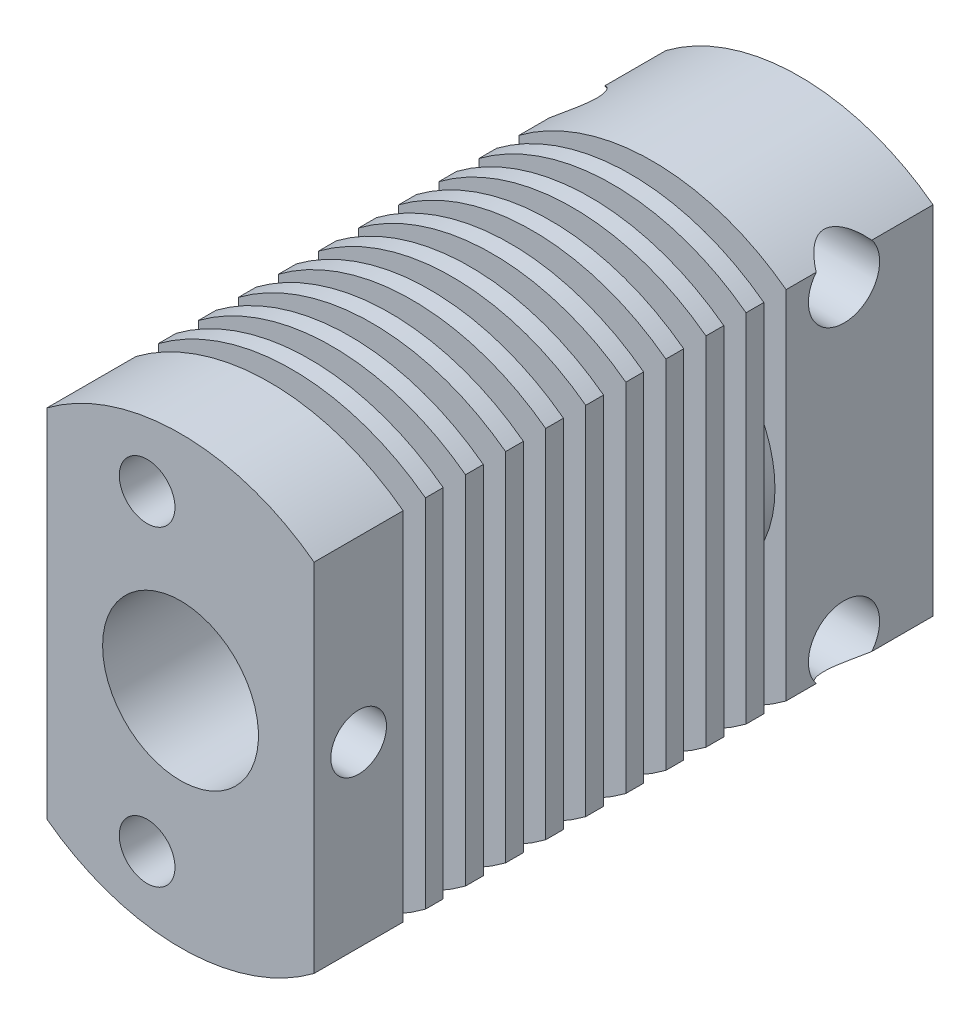
SolidWorks part; units mm, degrees
material "4032-T6"
ref_plane "Alzado" through (0, 0, 0) normal (0, 0, 1) x (1, 0, 0)
ref_plane "Planta" through (0, 0, 0) normal (0, 1, 0) x (1, 0, 0)
ref_plane "Vista lateral" through (0, 0, 0) normal (1, 0, 0) x (0, 0, -1)
sketch "Croquis1" plane through (0, 0, 0) normal (0, 1, 0) x (1, 0, 0)
  line L0 (4.3, -9.8) -> (0, -9.8)
  line L1 (0, -9.8) -> (0, -10.8)
  line L2 (0, -10.8) -> (4.3, -10.8)
  line L3 (4.3, -10.8) -> (4.3, -9.8)
  line L4 (0, -9.8) -> (0, -10.8) construction
revolve "Revolución1" add sketch "Croquis1" angle 360 about L4
ref_plane "Plano1" through (0, 0, 9.8) normal (0, 0, 1) x (1, 0, 0)
sketch "Croquis2" plane through (0, 0, 9.8) normal (0, 0, 1) x (1, 0, 0)
  line L0 (-6, 8) -> (-6, -8)
  line L1 (6, -8) -> (6, 8)
  arc A0 (6, 8) -> (-6, 8) centre (0, 0) ccw
  arc A1 (-6, -8) -> (6, -8) centre (0, 0) ccw
extrude "Saliente-Extruir1" add sketch "Croquis2" against normal blind 0.8
ref_plane "Plano2" through (0, 0, 10.8) normal (0, 0, -1) x (-1, 0, 0)
sketch "Croquis3" plane through (0, 0, 10.8) normal (0, 0, -1) x (-1, 0, 0)
  line L0 (6, -8) -> (6, 8)
  line L1 (-6, 8) -> (-6, -8)
  arc A0 (6, 8) -> (-6, 8) centre (0, 0) ccw
  arc A1 (-6, -8) -> (6, -8) centre (0, 0) ccw
extrude "Saliente-Extruir2" add sketch "Croquis3" against normal blind 0.8
sketch "Croquis4" plane through (0, 0, 11.6) normal (0, 0, 1) x (1, 0, 0)
  circle A0 centre (0, 0) radius 4.3
extrude "Saliente-Extruir3" add sketch "Croquis4" along normal blind 1
sketch "Croquis5" plane through (0, 0, 9) normal (0, 0, -1) x (-1, 0, 0)
  circle A0 centre (0, 0) radius 4.3
extrude "Saliente-Extruir4" add sketch "Croquis5" along normal blind 1
ref_plane "Plano3" through (0, 0, 8) normal (0, 0, 1) x (1, 0, 0)
sketch "Croquis6" plane through (0, 0, 8) normal (0, 0, 1) x (1, 0, 0)
  line L0 (-6, 8) -> (-6, -8)
  line L1 (6, -8) -> (6, 8)
  arc A0 (6, 8) -> (-6, 8) centre (0, 0) ccw
  arc A1 (-6, -8) -> (6, -8) centre (0, 0) ccw
extrude "Saliente-Extruir5" add sketch "Croquis6" against normal blind 0.8
ref_plane "Plano4" through (0, 0, 12.6) normal (0, 0, -1) x (-1, 0, 0)
sketch "Croquis7" plane through (0, 0, 12.6) normal (0, 0, -1) x (-1, 0, 0)
  line L0 (6, -8) -> (6, 8)
  line L1 (-6, 8) -> (-6, -8)
  arc A0 (6, 8) -> (-6, 8) centre (0, 0) ccw
  arc A1 (-6, -8) -> (6, -8) centre (0, 0) ccw
extrude "Saliente-Extruir6" add sketch "Croquis7" against normal blind 0.8
sketch "Croquis8" plane through (0, 0, 13.4) normal (0, 0, 1) x (1, 0, 0)
  circle A0 centre (0, 0) radius 4.3
extrude "Saliente-Extruir7" add sketch "Croquis8" along normal blind 1
sketch "Croquis9" plane through (0, 0, 7.2) normal (0, 0, -1) x (-1, 0, 0)
  circle A0 centre (0, 0) radius 4.3
extrude "Saliente-Extruir8" add sketch "Croquis9" along normal blind 1
ref_plane "Plano5" through (0, 0, 6.2) normal (0, 0, 1) x (1, 0, 0)
sketch "Croquis10" plane through (0, 0, 6.2) normal (0, 0, 1) x (1, 0, 0)
  line L0 (-6, 8) -> (-6, -8)
  line L1 (6, -8) -> (6, 8)
  arc A0 (6, 8) -> (-6, 8) centre (0, 0) ccw
  arc A1 (-6, -8) -> (6, -8) centre (0, 0) ccw
extrude "Saliente-Extruir9" add sketch "Croquis10" against normal blind 0.8
ref_plane "Plano6" through (0, 0, 14.4) normal (0, 0, -1) x (-1, 0, 0)
sketch "Croquis11" plane through (0, 0, 14.4) normal (0, 0, -1) x (-1, 0, 0)
  line L0 (6, -8) -> (6, 8)
  line L1 (-6, 8) -> (-6, -8)
  arc A0 (6, 8) -> (-6, 8) centre (0, 0) ccw
  arc A1 (-6, -8) -> (6, -8) centre (0, 0) ccw
extrude "Saliente-Extruir10" add sketch "Croquis11" against normal blind 0.8
sketch "Croquis12" plane through (0, 0, 15.2) normal (0, 0, 1) x (1, 0, 0)
  circle A0 centre (0, 0) radius 4.3
extrude "Saliente-Extruir11" add sketch "Croquis12" along normal blind 1
sketch "Croquis13" plane through (0, 0, 5.4) normal (0, 0, -1) x (-1, 0, 0)
  circle A0 centre (0, 0) radius 4.3
extrude "Saliente-Extruir12" add sketch "Croquis13" along normal blind 1
ref_plane "Plano7" through (0, 0, 4.4) normal (0, 0, 1) x (1, 0, 0)
sketch "Croquis14" plane through (0, 0, 4.4) normal (0, 0, 1) x (1, 0, 0)
  line L0 (6, -8) -> (6, 8)
  line L1 (-6, 8) -> (-6, -8)
  arc A0 (6, 8) -> (-6, 8) centre (0, 0) ccw
  arc A1 (-6, -8) -> (6, -8) centre (0, 0) ccw
extrude "Saliente-Extruir13" add sketch "Croquis14" against normal blind 0.8
ref_plane "Plano8" through (0, 0, 16.2) normal (0, 0, -1) x (-1, 0, 0)
sketch "Croquis15" plane through (0, 0, 16.2) normal (0, 0, -1) x (-1, 0, 0)
  line L0 (6, -8) -> (6, 8)
  line L1 (-6, 8) -> (-6, -8)
  arc A0 (6, 8) -> (-6, 8) centre (0, 0) ccw
  arc A1 (-6, -8) -> (6, -8) centre (0, 0) ccw
extrude "Saliente-Extruir14" add sketch "Croquis15" against normal blind 0.8
sketch "Croquis16" plane through (0, 0, 17) normal (0, 0, 1) x (1, 0, 0)
  circle A0 centre (0, 0) radius 4.3
extrude "Saliente-Extruir15" add sketch "Croquis16" along normal blind 1
sketch "Croquis17" plane through (0, 0, 3.6) normal (0, 0, -1) x (-1, 0, 0)
  circle A0 centre (0, 0) radius 5.5
extrude "Saliente-Extruir16" add sketch "Croquis17" along normal blind 1
ref_plane "Plano9" through (0, 0, 2.6) normal (0, 0, 1) x (1, 0, 0)
sketch "Croquis18" plane through (0, 0, 2.6) normal (0, 0, 1) x (1, 0, 0)
  line L0 (-6, 8) -> (-6, -8)
  line L1 (6, -8) -> (6, 8)
  arc A0 (6, 8) -> (-6, 8) centre (0, 0) ccw
  arc A1 (-6, -8) -> (6, -8) centre (0, 0) ccw
extrude "Saliente-Extruir17" add sketch "Croquis18" against normal blind 6.6
ref_plane "Plano10" through (0, 0, 18) normal (0, 0, -1) x (-1, 0, 0)
sketch "Croquis19" plane through (0, 0, 18) normal (0, 0, -1) x (-1, 0, 0)
  line L0 (-6, 8) -> (-6, -8)
  line L1 (6, -8) -> (6, 8)
  arc A0 (6, 8) -> (-6, 8) centre (0, 0) ccw
  arc A1 (-6, -8) -> (6, -8) centre (0, 0) ccw
extrude "Saliente-Extruir18" add sketch "Croquis19" against normal blind 0.8
sketch "Croquis20" plane through (0, 0, 18.8) normal (0, 0, 1) x (1, 0, 0)
  circle A0 centre (0, 0) radius 4.3
extrude "Saliente-Extruir19" add sketch "Croquis20" along normal blind 1
ref_plane "Plano11" through (0, 0, 19.8) normal (0, 0, -1) x (-1, 0, 0)
sketch "Croquis21" plane through (0, 0, 19.8) normal (0, 0, -1) x (-1, 0, 0)
  line L0 (6, -8) -> (6, 8)
  line L1 (-6, 8) -> (-6, -8)
  arc A0 (-6, -8) -> (6, -8) centre (0, 0) ccw
  arc A1 (6, 8) -> (-6, 8) centre (0, 0) ccw
extrude "Saliente-Extruir20" add sketch "Croquis21" against normal blind 4
sketch "Croquis22" plane through (0, 0, -4) normal (0, 0, -1) x (-1, 0, 0)
  circle A0 centre (0, 0) radius 4.9
extrude "Cortar-Extruir1" cut sketch "Croquis22" against normal blind 8
sketch "Croquis23" plane through (0, 0, 23.8) normal (0, 0, 1) x (1, 0, 0)
  circle A0 centre (0, 0) radius 3.5
extrude "Cortar-Extruir2" cut sketch "Croquis23" against normal blind 16.7
sketch "Croquis24" plane through (0, 0, 4) normal (0, 0, -1) x (-1, 0, 0)
  circle A0 centre (0, 0) radius 4.1
extrude "Cortar-Extruir3" cut sketch "Croquis24" against normal blind 1.6 draft 45
sketch "Croquis25" plane through (0, 0, 7.1) normal (0, 0, 1) x (1, 0, 0)
  circle A0 centre (0, 0) radius 2.5
extrude "Cortar-Extruir4" cut sketch "Croquis25" against normal blind 1.5
hole_wizard "Diámetro de taladro Ø2.5 (2.5)1" positions "Croquis27" profile "Croquis26" hole size "Ø2.5" standard "Ansi Metric"
sketch "Croquis27" plane through (0, 0, 23.8) normal (0, 0, 1) x (1, 0, 0)
  point P0 (-1.5, -7)
  point P1 (-1.5, 7)
sketch "Croquis26" plane through (-1.5, -7, 23.8) normal (1, 0, 0) x (0, -1, 0)
  line L0 (0, 0) -> (0, 4)
  line L1 (0, 4) -> (1.25, 4)
  line L2 (1.25, 4) -> (1.25, 0)
  line L5 (1.25, 0) -> (0, 0)
  line L11 (0, -6.35) -> (0, 107.95) construction
  dimension "Diámetro de taladro hasta el siguiente" = 2.5
  dimension "Profundidad de taladro hasta el siguiente" = 4
hole_wizard "Diámetro de taladro Ø2.5 (2.5)2" positions "Croquis29" profile "Croquis28" hole size "Ø2.5" standard "Ansi Metric"
sketch "Croquis29" plane through (6, 0, 0) normal (1, 0, 0) x (0, 0, -1)
  point P0 (-21.8, 0)
sketch "Croquis28" plane through (6, 0, 21.8) normal (0, 1, 0) x (0, 0, -1)
  line L0 (0, 0) -> (0, 2.5)
  line L1 (0, 2.5) -> (1.25, 2.5)
  line L2 (1.25, 2.5) -> (1.25, 0)
  line L5 (1.25, 0) -> (0, 0)
  line L11 (0, -6.35) -> (0, 107.95) construction
  dimension "Diámetro de taladro hasta el siguiente" = 2.5
  dimension "Profundidad de taladro hasta el siguiente" = 2.5
hole_wizard "Diámetro de taladro Ø3.2 (3.2)1" positions "Croquis31" profile "Croquis30" hole size "Ø3.2" standard "Ansi Metric"
sketch "Croquis31" plane through (-6, 0, 0) normal (-1, 0, 0) x (0, 0, 1)
  point P0 (0, 7)
sketch "Croquis30" plane through (-6, 7, 0) normal (0, 1, 0) x (0, 0, 1)
  line L0 (0, 0) -> (0, 12)
  line L1 (0, 12) -> (1.6, 12)
  line L2 (1.6, 12) -> (1.6, 0)
  line L5 (1.6, 0) -> (0, 0)
  line L11 (0, -6.35) -> (0, 107.95) construction
  dimension "Diámetro de taladro hasta el siguiente" = 3.2
  dimension "Profundidad de taladro hasta el siguiente" = 12
hole_wizard "Diámetro de taladro Ø3.2 (3.2)2" positions "Croquis33" profile "Croquis32" hole size "Ø3.2" standard "Ansi Metric"
sketch "Croquis33" plane through (6, 0, 0) normal (1, 0, 0) x (0, 0, -1)
  point P0 (0, -7)
sketch "Croquis32" plane through (6, -7, 0) normal (0, 1, 0) x (0, 0, -1)
  line L0 (0, 0) -> (0, 12)
  line L1 (0, 12) -> (1.6, 12)
  line L2 (1.6, 12) -> (1.6, 0)
  line L5 (1.6, 0) -> (0, 0)
  line L11 (0, -6.35) -> (0, 107.95) construction
  dimension "Diámetro de taladro hasta el siguiente" = 3.2
  dimension "Profundidad de taladro hasta el siguiente" = 12
fillet "Redondeo1" radius 1 2 edges at (-2.5, 0, 5.6) (4.1, 0, 4)
